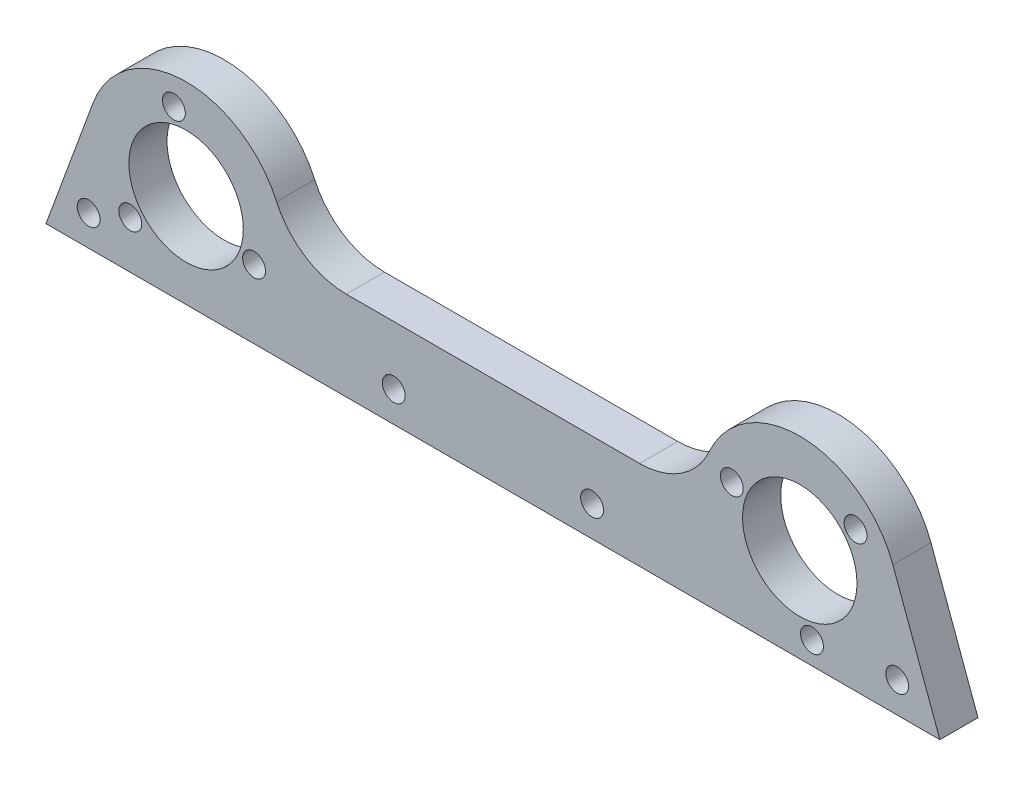
SolidWorks part; units mm, degrees
ref_plane "前视基准面" through (0, 0, 0) normal (0, 0, 1) x (1, 0, 0)
ref_plane "上视基准面" through (0, 0, 0) normal (0, 1, 0) x (1, 0, 0)
ref_plane "右视基准面" through (0, 0, 0) normal (1, 0, 0) x (0, 0, -1)
sketch "草图1" plane through (0, 0, 0) normal (0, 0, 1) x (1, 0, 0)
  line L0 (-18.3632, 0) -> (18.3632, 0)
  line L4 (-18.3632, 0) -> (-12.2038, 16.7797)
  line L5 (12.2038, 16.7797) -> (18.3632, 0)
  arc A0 (12.2038, 16.7797) -> (-12.2038, 16.7797) centre (0, 12.3) ccw
  point P7 (0, 50.0255)
  dimension "D1" = 13
  dimension "D2" = 12.3
extrude "凸台-拉伸1" add sketch "草图1" along normal mid plane 5 from offset 1.25
sketch "草图2" plane through (0, 0, 3.75) normal (0, 0, 1) x (1, 0, 0)
  circle A0 centre (0, 12.3) radius 7.5
  arc A1 (12.2038, 16.7797) -> (-12.2038, 16.7797) centre (0, 12.3) ccw construction
  dimension "D1" = 15
extrude "切除-拉伸1" cut sketch "草图2" against normal through all
pattern_linear "阵列(线性)1" count 2 spacing 80.45 along (1, 0, 0) of bodies 107 110
sketch "草图3" plane through (0, 0, -1.25) normal (0, 0, -1) x (-1, 0, 0)
  line L0 (-18.3632, 0) -> (-12.2038, 16.7797) construction
  line L1 (-14.0739, 11.6851) -> (-66.3761, 11.6851)
  line L2 (-14.0739, 11.6851) -> (-14.0739, 0)
  line L3 (-14.0739, 0) -> (-66.3761, 0)
  line L4 (-66.3761, 11.6851) -> (-66.3761, 0)
  line L5 (-62.0868, 0) -> (-98.8132, 0) construction
  line L7 (-68.2462, 16.7797) -> (-62.0868, 0) construction
  point P8 (0, 0)
  point P11 (0, 0)
  point P12 (0, 0)
extrude "凸台-拉伸2" add sketch "草图3" against normal up to surface (5 mm away) up to face at (87.95, 12.3, 3.75)
fillet "圆角1" radius 10 2 edges at (14.0739, 11.6851, 1.25) (66.3761, 11.6851, 1.25)
sketch "草图4" plane through (0, 0, -1.25) normal (0, 0, -1) x (-1, 0, 0)
  circle A0 centre (1.5984, 21.6646) radius 1.5 construction
  circle A1 centre (7.3107, 6.2335) radius 1.5 construction
  circle A2 centre (-8.9092, 9.002) radius 1.5 construction
  circle A3 centre (1.5984, 21.6646) radius 1.5
  circle A4 centre (7.3107, 6.2335) radius 1.5
  circle A5 centre (-8.9092, 9.002) radius 1.5
  circle A6 centre (-71.5408, 15.598) radius 1.5 construction
  circle A7 centre (-82.0484, 2.9354) radius 1.5 construction
  circle A8 centre (-87.7607, 18.3665) radius 1.5 construction
  circle A9 centre (-71.5408, 15.598) radius 1.5
  circle A10 centre (-82.0484, 2.9354) radius 1.5
  circle A11 centre (-87.7607, 18.3665) radius 1.5
extrude "切除-拉伸2" cut sketch "草图4" against normal through all
sketch "草图5" plane through (0, 0, -1.25) normal (0, 0, -1) x (-1, 0, 0)
  line L0 (18.3632, 0) -> (-98.8132, 0) construction
  line L1 (-20.9981, 11.6851) -> (-59.4519, 11.6851) construction
  line L2 (-40.225, 11.6851) -> (-40.225, 0) construction
  circle A0 centre (-93.225, 4) radius 1.5
  circle A1 centre (-53.225, 4) radius 1.5
  circle A4 centre (12.775, 4) radius 1.5
  circle A5 centre (-27.225, 4) radius 1.5
  point P14 (-53.225, 4)
  dimension "D1" = 3
  dimension "D2" = 4
  dimension "D3" = 53
  dimension "D4" = 13
extrude "切除-拉伸3" cut sketch "草图5" against normal through all
